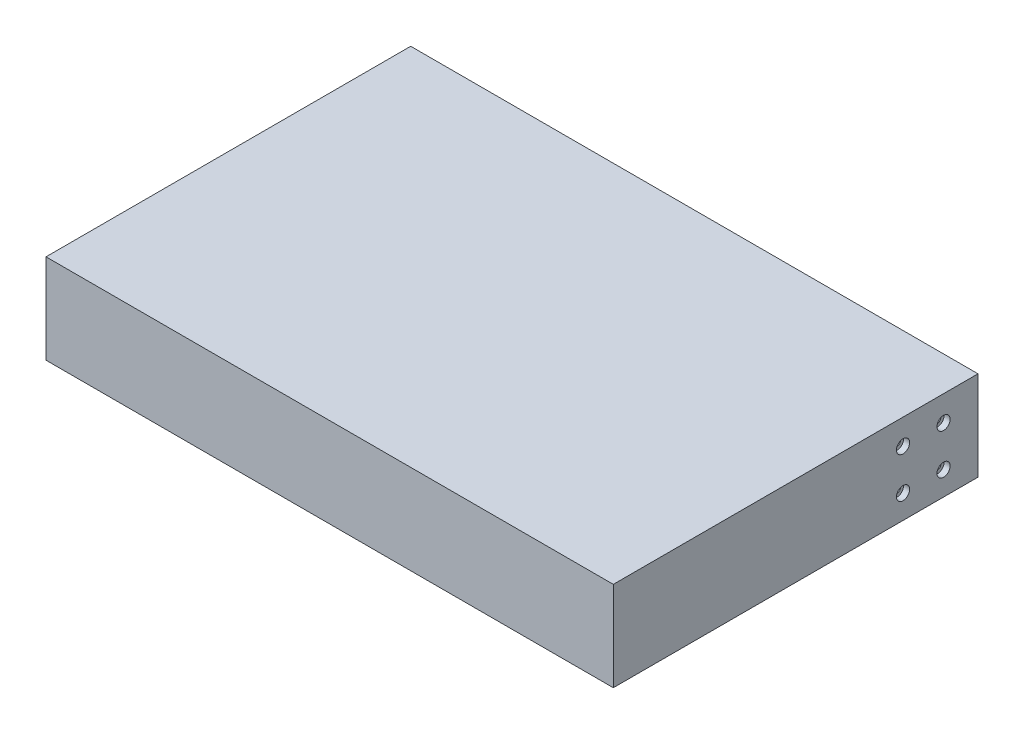
SolidWorks part; units mm, degrees
ref_plane "Front Plane" through (0, 0, 0) normal (0, 0, 1) x (1, 0, 0)
ref_plane "Top Plane" through (0, 0, 0) normal (0, 1, 0) x (1, 0, 0)
ref_plane "Right Plane" through (0, 0, 0) normal (1, 0, 0) x (0, 0, -1)
sketch "Sketch1" plane through (0, 0, 0) normal (0, 0, 1) x (1, 0, 0)
  line L1 (-140, 22.1) -> (140, 22.1)
  line L2 (-140, 22.1) -> (-140, -22.1)
  line L3 (-140, -22.1) -> (140, -22.1)
  line L4 (140, 22.1) -> (140, -22.1)
  line L5 (-140, 22.1) -> (140, -22.1) construction
  line L6 (-140, -22.1) -> (140, 22.1) construction
  point P0 (0, 0)
  dimension "D1" = 280
  dimension "D2" = 44.2
extrude "Boss-Extrude1" add sketch "Sketch1" along normal blind 180
sketch "Sketch2" plane through (0, 0, 0) normal (0, 0, -1) x (-1, 0, 0)
  line L0 (-78.987, -8.4231) -> (72.0504, -8.4231) construction
  text T0 "TRENDNET  TEG-S24DG" font "Century Gothic" height in points 42
extrude "Cut-Extrude1" cut sketch "Sketch2" against normal blind 10
sketch "Sketch5" plane through (-140, 0, 0) normal (-1, 0, 0) x (0, 0, 1)
  line L0 (0, 22.1) -> (0, -22.1) construction
  line L1 (180, 22.1) -> (0, 22.1) construction
  point P0 (17, 9.6)
  point P2 (37, 9.6)
  point P4 (17, -10.4)
  point P6 (37, -10.4)
  point P13 (0, 0)
  point P14 (0, 0)
  point P15 (0, 0)
  point P16 (0, 0)
  dimension "D1" = 17
  dimension "D2" = 20
  dimension "D3" = 20
  dimension "D4" = 12.5
hole_wizard "CBORE for M3 SHCS1" positions "Sketch5" profile "Sketch4" counterbore size "M3" standard "ANSI Metric"
sketch "Sketch4" plane through (-140, 9.6, 17) normal (0, 1, 0) x (0, 0, 1)
  line L0 (0, 0) -> (0, 11.1215)
  line L1 (0, 11.1215) -> (1.7, 10.1)
  line L2 (1.7, 10.1) -> (1.7, 3)
  line L3 (1.7, 3) -> (3.25, 3)
  line L4 (3.25, 3) -> (3.25, 0)
  line L5 (3.25, 0) -> (0, 0)
  line L10 (0, 11.1215) -> (-1.7, 10.1) construction
  line L11 (0, -6.35) -> (0, 107.95) construction
  dimension "Hole Dia." = 3.4
  dimension "Hole Depth" = 10.1
  dimension "C'Bore Dia." = 6.5
  dimension "C'Bore Depth" = 3
  dimension "Drill Angle" = 118
mirror "Mirror1" about plane through (0, 0, 0) normal (1, 0, 0) of "CBORE for M3 SHCS1"
